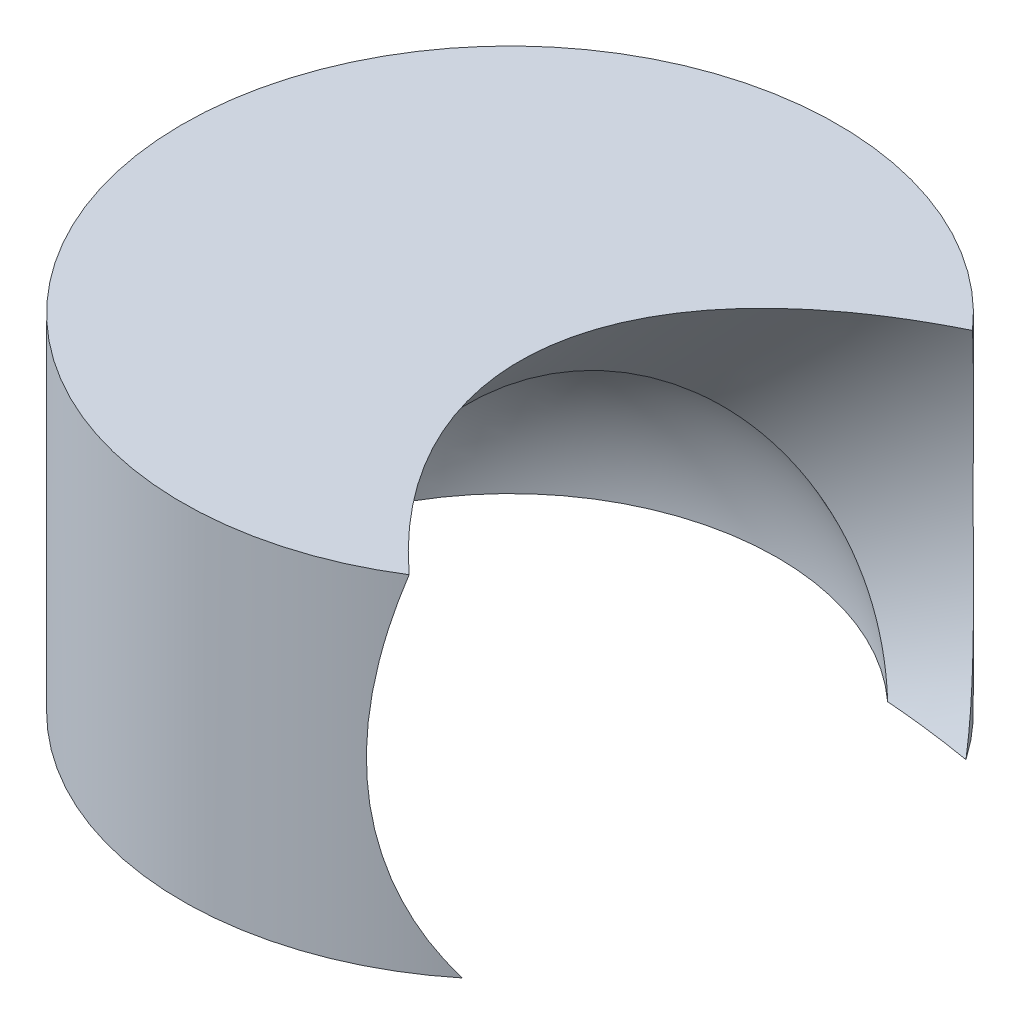
SolidWorks part; units mm, degrees
other "Moving Steel Cup Liner 1"
ref_plane "Front Plane" through (0, 0, 0) normal (0, 0, 1) x (1, 0, 0)
ref_plane "Top Plane" through (0, 0, 0) normal (0, 1, 0) x (1, 0, 0)
ref_plane "Right Plane" through (0, 0, 0) normal (1, 0, 0) x (0, 0, -1)
sketch3d "Keyed Back Sketch datum points"
  point P0 (-56.2917, -97, 0)
  point P1 (-46.2917, -97, 0)
  point P2 (-56.2917, -97, 10)
ref_plane "Keyed Back Sketch plane" through (0, -97, 0) normal (0, -1, 0) x (-1, 0, 0)
sketch "Keyed Back Sketch" plane through (0, -97, 0) normal (0, -1, 0) x (-1, 0, 0)
  line L0 (79.2724, 17.3324) -> (79.2724, 12.6676)
  arc A0 (79.2724, 12.6676) -> (79.2724, 17.3324) centre (82.2724, 15) ccw
extrude "Keyed Back" add sketch "Keyed Back Sketch" along normal blind 0.7 separate body
sketch3d "Cup Blank Sketch datum points"
  point P0 (-56.2917, -97.7, 0)
  point P1 (-46.2917, -97.7, 0)
  point P2 (-56.2917, -97.7, 10)
ref_plane "Cup Blank Sketch plane" through (0, -97.7, 0) normal (0, -1, 0) x (-1, 0, 0)
sketch "Cup Blank Sketch" plane through (0, -97.7, 0) normal (0, -1, 0) x (-1, 0, 0)
  circle A0 centre (82.2724, 15) radius 3.8
extrude "Cup Blank" add sketch "Cup Blank Sketch" along normal blind 3.3
sketch3d "Spherical Bearing Seat axis line"
  line L0 (-82.2724, -101, -25) -> (-82.2724, -101, -5) construction
ref_axis "Spherical Bearing Seat axis" through (-82.2724, -101, -25) along (0, 0, 1)
sketch3d "Spherical Bearing Seat profile datum points"
  point P0 (-82.2724, -101, -15)
  point P1 (-72.2724, -101, -15)
  point P2 (-82.2724, -101, -5)
ref_plane "Spherical Bearing Seat profile plane" through (0, -101, 0) normal (0, -1, 0) x (-1, 0, 0)
sketch "Spherical Bearing Seat profile" plane through (0, -101, 0) normal (0, -1, 0) x (-1, 0, 0)
  line L0 (82.2724, 11.9) -> (82.2724, 18.1)
  arc A0 (82.2724, 18.1) -> (82.2724, 11.9) centre (82.2724, 15) ccw
revolve "Spherical Bearing Seat" cut sketch "Spherical Bearing Seat profile" angle 360 about axis through (-82.2724, -101, -25) along (0, 0, 1)
sketch3d "Articulation Throat axis line"
  line L0 (-90.6158, -106.3831, -16.1872) -> (-73.929, -95.6169, -13.8128) construction
ref_axis "Articulation Throat axis" through (-90.6158, -106.3831, -16.1872) along (0.8343, 0.5383, 0.1187)
sketch3d "Articulation Throat Sketch datum points"
  point P0 (-82.2724, -101, -15)
  point P1 (-82.2724, -98.8462, -24.7653)
  point P2 (-73.929, -95.6169, -13.8128)
ref_plane "Articulation Throat Sketch plane" through (21.8481, -32.2924, -7.1221) normal (0.5512, -0.8148, -0.1797) x (-0.8343, -0.5383, -0.1187)
sketch "Articulation Throat Sketch" plane through (21.8481, -32.2924, -7.1221) normal (0.5512, -0.8148, -0.1797) x (-0.8343, -0.5383, -0.1187)
  line L0 (124.7935, -7.105) -> (124.7935, -4.805)
  line L1 (124.7935, -4.805) -> (101.7935, 1.915)
  line L2 (101.7935, 1.915) -> (101.7935, -7.105)
  line L3 (101.7935, -7.105) -> (124.7935, -7.105)
revolve "Articulation Throat" cut sketch "Articulation Throat Sketch" angle 360 about axis through (-90.6158, -106.3831, -16.1872) along (0.8343, 0.5383, 0.1187)
